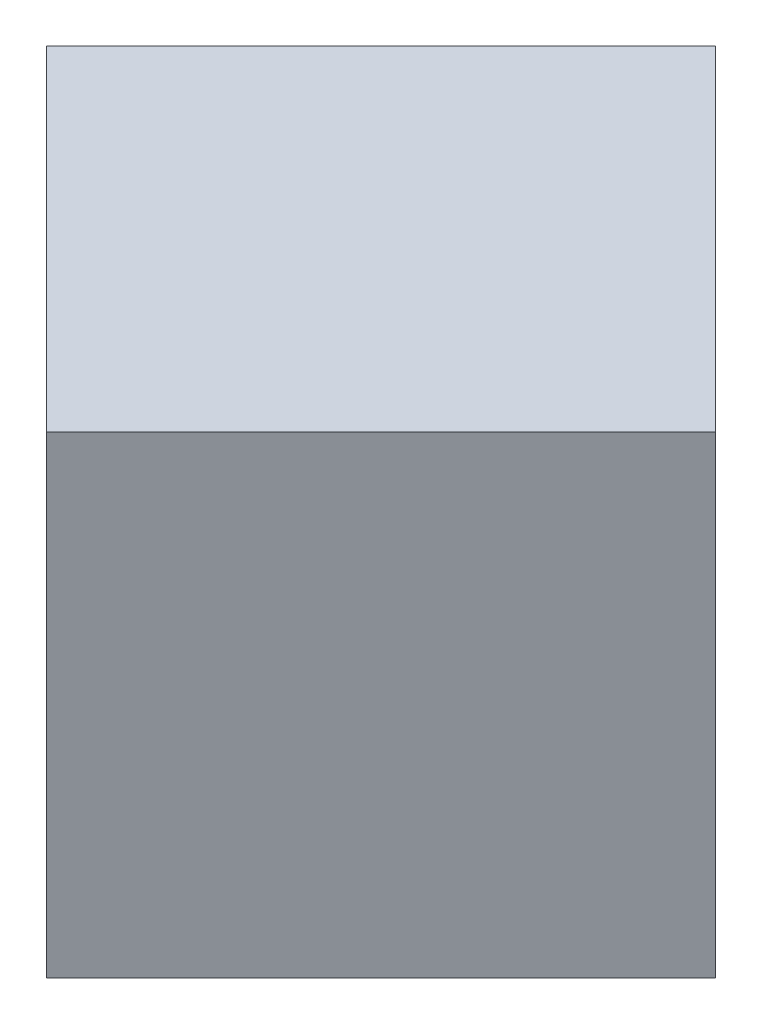
SolidWorks part; units mm, degrees
ref_plane "Front Plane" through (0, 0, 0) normal (0, 0, 1) x (1, 0, 0)
ref_plane "Top Plane" through (0, 0, 0) normal (0, 1, 0) x (1, 0, 0)
ref_plane "Right Plane" through (0, 0, 0) normal (1, 0, 0) x (0, 0, -1)
sketch "Sketch1" plane through (0, 0, 0) normal (0, 1, 0) x (1, 0, 0)
  line L0 (-86.3924, 69.1139) -> (95.443, 69.1139)
  line L1 (0, -45.9619) -> (45.9619, 0)
  line L2 (0, -45.9619) -> (-45.9619, 0)
  line L3 (-45.9619, 0) -> (0, 45.9619)
  line L4 (45.9619, 0) -> (0, 45.9619)
  line L5 (0, -45.9619) -> (0, 45.9619) construction
  line L6 (-45.9619, 0) -> (45.9619, 0) construction
  point P0 (0, 0)
  dimension "D1" = 65
  dimension "D2" = 65
  dimension "D3" = 45
extrude "Boss-Extrude3" add sketch "Sketch1" along normal blind 65 contours L1 L4 L3 L2
sketch3d "3DSketch1"
  point P3 (0, 32.5, 45.9619)
